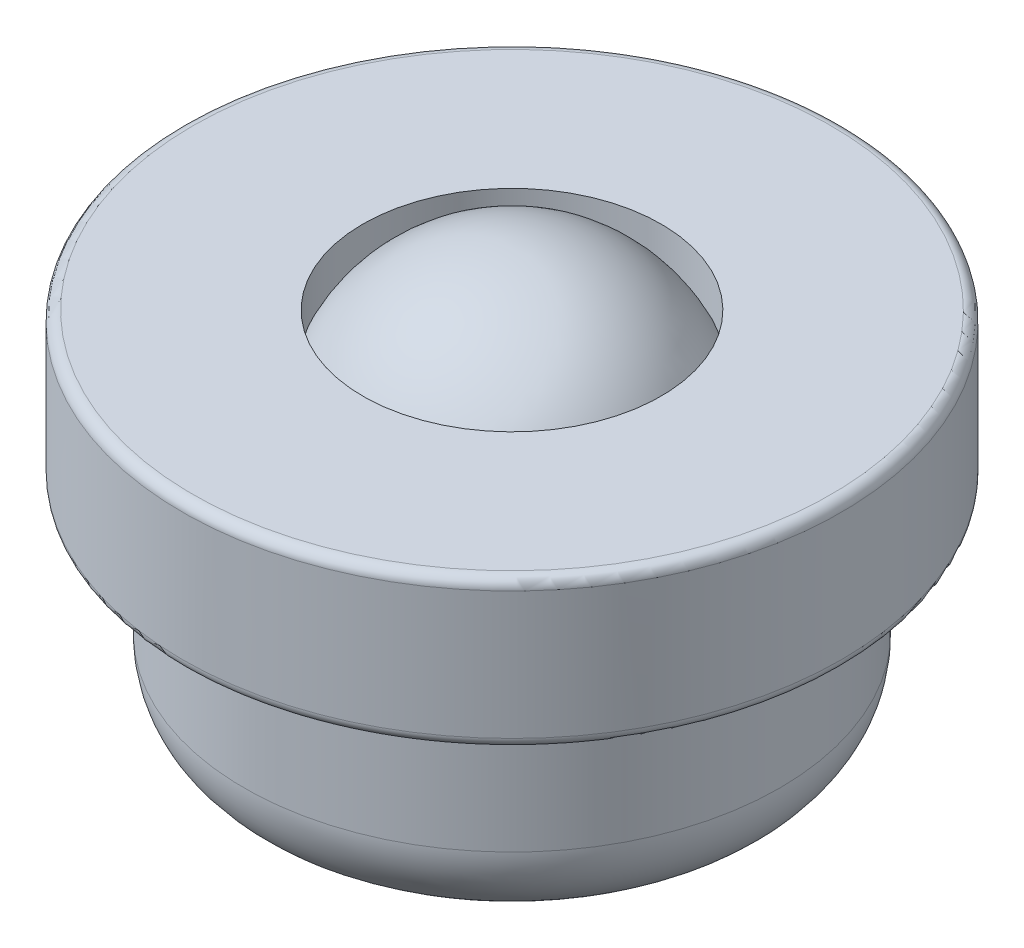
SolidWorks part; units mm, degrees
ref_plane "Plan de face" through (0, 0, 0) normal (0, 0, 1) x (1, 0, 0)
ref_plane "Plan de dessus" through (0, 0, 0) normal (0, 1, 0) x (1, 0, 0)
ref_plane "Plan de droite" through (0, 0, 0) normal (1, 0, 0) x (0, 0, -1)
sketch "Esquisse1" plane through (0, 0, 0) normal (0, 0, 1) x (1, 0, 0)
  line L0 (0, 0) -> (-4.5, 0)
  line L1 (-6.5, 2) -> (-6.5, 5.2)
  line L2 (-6.5, 5.2) -> (-8, 5.2)
  line L3 (-8, 5.2) -> (-8, 8.8)
  line L4 (-8, 8.8) -> (-3.6208, 8.8)
  line L5 (-4.5, 2) -> (-6.5, 2) construction
  line L6 (-4.5, 2) -> (-4.5, 0) construction
  line L7 (0, 0) -> (0, 10.1) construction
  line L8 (-3.6208, 8.8) -> (-3.6208, 7.8)
  line L9 (0, 10.1) -> (0, 0)
  arc A0 (-4.5, 0) -> (-6.5, 2) centre (-4.5, 2) cw
  arc A1 (-3.6208, 7.8) -> (0, 10.1) centre (0, 6.1) cw
  circle A2 centre (0, 6.1) radius 4 construction
  dimension "D3" = 8
  dimension "D7" = 2
  dimension "D1" = 8
  dimension "D2" = 6.5
  dimension "D4" = 10.1
  dimension "D5" = 3.6
  dimension "D6" = 1.3
  dimension "D8" = 1
revolve "Révolution1" add sketch "Esquisse1" angle 360 about L9
fillet "Congé1" radius 0.25 2 edges at (-8, 5.2, 0) (-8, 8.8, 0)
